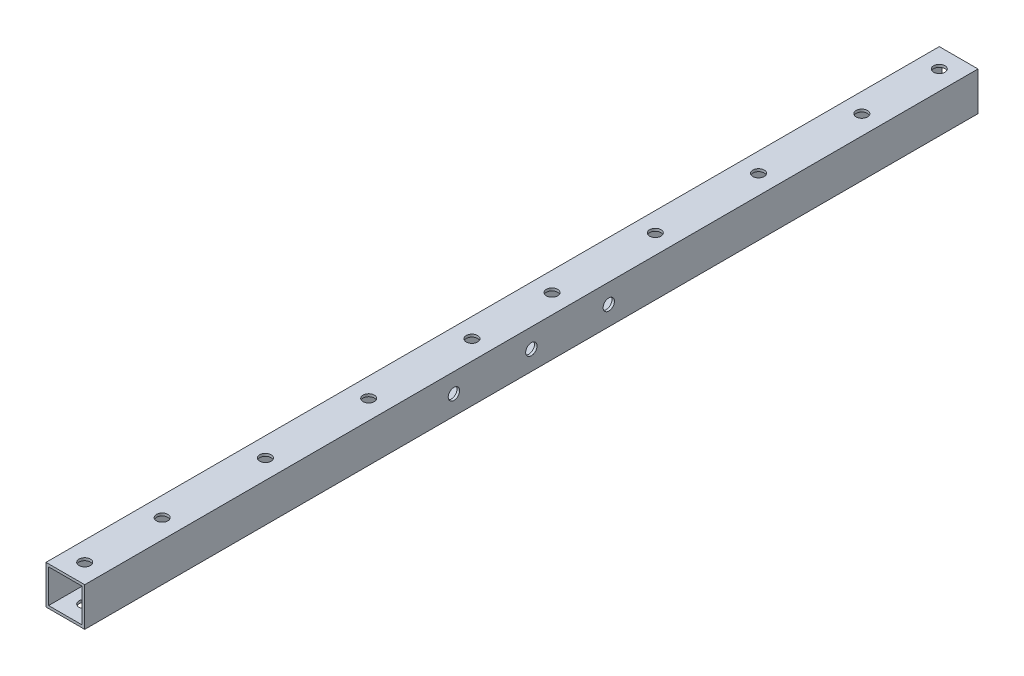
SolidWorks part; units mm, degrees
ref_plane "前视基准面" through (0, 0, 0) normal (0, 0, 1) x (1, 0, 0)
ref_plane "上视基准面" through (0, 0, 0) normal (0, 1, 0) x (1, 0, 0)
ref_plane "右视基准面" through (0, 0, 0) normal (1, 0, 0) x (0, 0, -1)
other "Configuration Table"
sketch "草图1" plane through (0, 0, 0) normal (0, 0, 1) x (1, 0, 0)
  line L1 (-7.5, 7.5) -> (7.5, 7.5)
  line L2 (-7.5, 7.5) -> (-7.5, -7.5)
  line L3 (-7.5, -7.5) -> (7.5, -7.5)
  line L4 (7.5, 7.5) -> (7.5, -7.5)
  line L5 (-7.5, 7.5) -> (7.5, -7.5) construction
  line L6 (-7.5, -7.5) -> (7.5, 7.5) construction
  line L7 (-6.5, 6.5) -> (6.5, 6.5)
  line L8 (-6.5, 6.5) -> (-6.5, -6.5)
  line L9 (-6.5, -6.5) -> (6.5, -6.5)
  line L10 (6.5, 6.5) -> (6.5, -6.5)
  line L11 (-6.5, 6.5) -> (6.5, -6.5) construction
  line L12 (-6.5, -6.5) -> (6.5, 6.5) construction
  point P0 (0, 0)
  point P5 (0, 0)
  dimension "D1" = 15
  dimension "D2" = 15
  dimension "D3" = 1
  dimension "D4" = 1
extrude "凸台-拉伸1" add sketch "草图1" along normal blind 346
sketch "草图3" plane through (0, 7.5, 0) normal (0, 1, 0) x (1, 0, 0)
  line L0 (0, 0) -> (0, -346) construction
  line L1 (7.5, 0) -> (-7.5, 0) construction
  line L2 (7.5, -346) -> (-7.5, -346) construction
  line L3 (-7.5, -173) -> (7.5, -173) construction
  line L4 (-7.5, -346) -> (-7.5, 0) construction
  line L5 (7.5, -346) -> (7.5, 0) construction
  circle A0 centre (0, -338.5) radius 2.2
  circle A1 centre (0, -7.5) radius 2.2
  circle A2 centre (0, -37.5) radius 2.2
  circle A3 centre (0, -308.5) radius 2.2
  circle A4 centre (0, -77.5) radius 2.2
  circle A5 centre (0, -117.5) radius 2.2
  circle A6 centre (0, -228.5) radius 2.2
  circle A7 centre (0, -268.5) radius 2.2
  circle A8 centre (0, -157.5) radius 2.2
  circle A10 centre (0, -188.5) radius 2.2
  dimension "D1" = 4.4
  dimension "D2" = 7.5
  dimension "D3" = 4.4
  dimension "D5" = 40
  dimension "D7" = 40
  dimension "D4" = 30
  dimension "D6" = 40
extrude "切除-拉伸2" cut sketch "草图3" against normal blind 55
sketch "草图4" plane through (7.5, 0, 0) normal (1, 0, 0) x (0, 0, -1)
  line L0 (-346, 0) -> (0, 0) construction
  line L1 (-346, -7.5) -> (-346, 7.5) construction
  line L2 (-173, 7.5) -> (-173, -7.5) construction
  line L3 (-346, 7.5) -> (0, 7.5) construction
  line L4 (-346, -7.5) -> (0, -7.5) construction
  circle A0 centre (-173, 0) radius 2.2
  circle A1 centre (-203, 0) radius 2.2
  circle A2 centre (-143, 0) radius 2.2
  dimension "D1" = 4.4
  dimension "D2" = 60
  dimension "D3" = 4.4
extrude "切除-拉伸3" cut sketch "草图4" against normal blind 55
